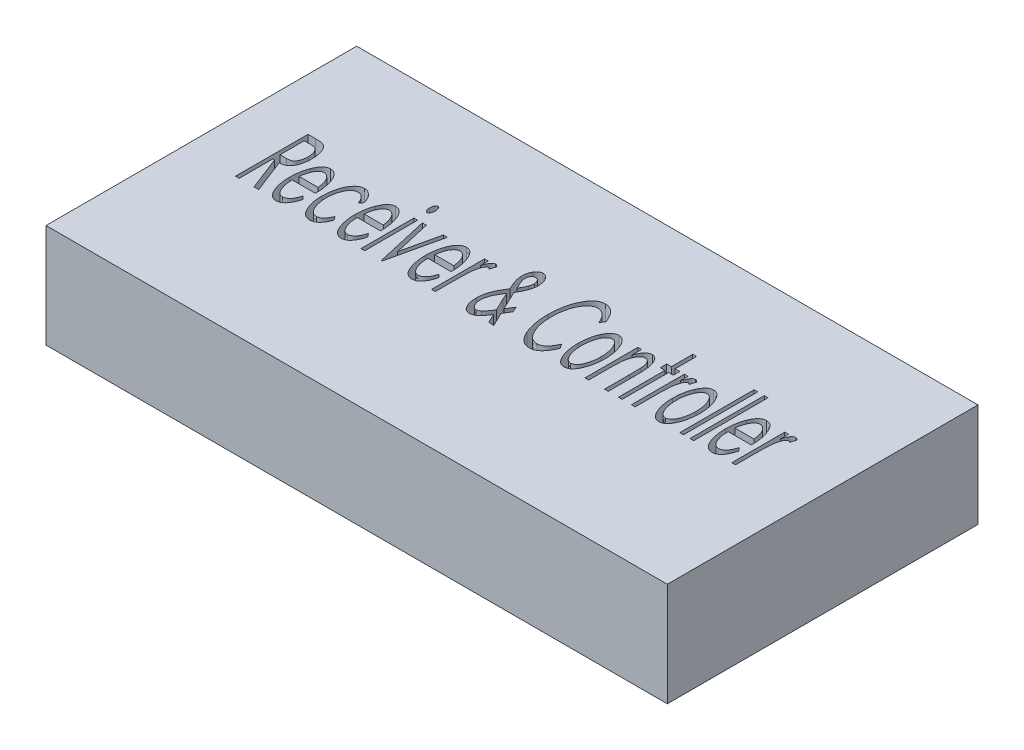
SolidWorks part; units mm, degrees
ref_plane "Front Plane" through (0, 0, 0) normal (0, 0, 1) x (1, 0, 0)
ref_plane "Top Plane" through (0, 0, 0) normal (0, 1, 0) x (1, 0, 0)
ref_plane "Right Plane" through (0, 0, 0) normal (1, 0, 0) x (0, 0, -1)
sketch "Sketch1" plane through (0, 0, 0) normal (0, 1, 0) x (1, 0, 0)
  line L1 (-21.4224, 8.2974) -> (8.5776, 8.2974)
  line L2 (-21.4224, 8.2974) -> (-21.4224, -6.7026)
  line L3 (-21.4224, -6.7026) -> (8.5776, -6.7026)
  line L4 (8.5776, 8.2974) -> (8.5776, -6.7026)
  dimension "D1" = 30
  dimension "D2" = 15
extrude "Boss-Extrude1" add sketch "Sketch1" along normal blind 5
sketch "Sketch2" plane through (0, 5, 0) normal (0, 1, 0) x (1, 0, 0)
  text T0 "Receiver & Controller" font "Century Gothic" height 3.5
extrude "Cut-Extrude1" cut sketch "Sketch2" against normal blind 2
